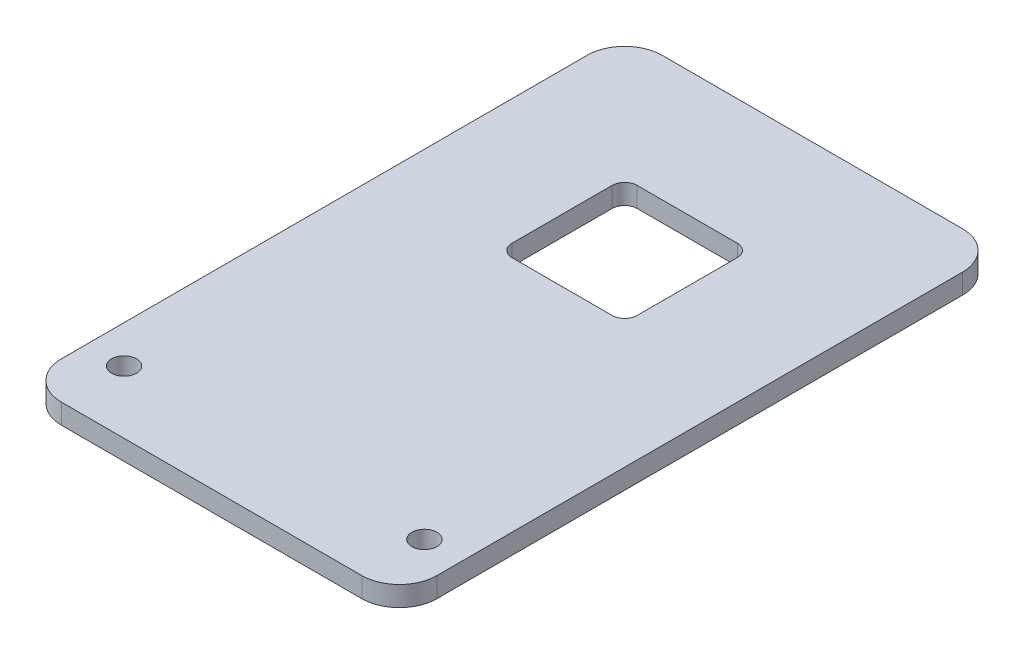
SolidWorks part; units mm, degrees
ref_plane "前视基准面" through (0, 0, 0) normal (0, 0, 1) x (1, 0, 0)
ref_plane "上视基准面" through (0, 0, 0) normal (0, 1, 0) x (1, 0, 0)
ref_plane "右视基准面" through (0, 0, 0) normal (1, 0, 0) x (0, 0, -1)
other "Configuration Table"
sketch "草图1" plane through (0, 0, 0) normal (0, 1, 0) x (1, 0, 0)
  line L1 (-15, -24) -> (15, -24)
  line L2 (-15, -24) -> (-15, 24)
  line L3 (-15, 24) -> (15, 24)
  line L4 (15, -24) -> (15, 24)
  line L5 (-15, -24) -> (15, 24) construction
  line L6 (-15, 24) -> (15, -24) construction
  line L7 (-5, 4) -> (5, 4)
  line L8 (-5, 4) -> (-5, 14)
  line L9 (-5, 14) -> (5, 14)
  line L10 (5, 4) -> (5, 14)
  line L11 (-5, 4) -> (5, 14) construction
  line L12 (-5, 14) -> (5, 4) construction
  circle A0 centre (-12, -19) radius 1
  circle A1 centre (12, -19) radius 1
  point P0 (0, 0)
  point P10 (0, 9)
  dimension "D3" = 2
  dimension "D4" = 2
  dimension "D5" = 3
  dimension "D6" = 3
  dimension "D7" = 43
  dimension "D8" = 43
  dimension "D1" = 30
  dimension "D2" = 48
  dimension "D9" = 10
  dimension "D10" = 10
  dimension "D11" = 15
  dimension "D12" = 15
extrude "凸台-拉伸1" add sketch "草图1" along normal blind 1.6
fillet "圆角1" radius 3 4 edges at (-15, 0.8, -24) (-15, 0.8, 24) (15, 0.8, -24) (15, 0.8, 24)
fillet "圆角2" radius 1 4 edges at (-5, 0.8, -14) (-5, 0.8, -4) (5, 0.8, -4) (5, 0.8, -14)
